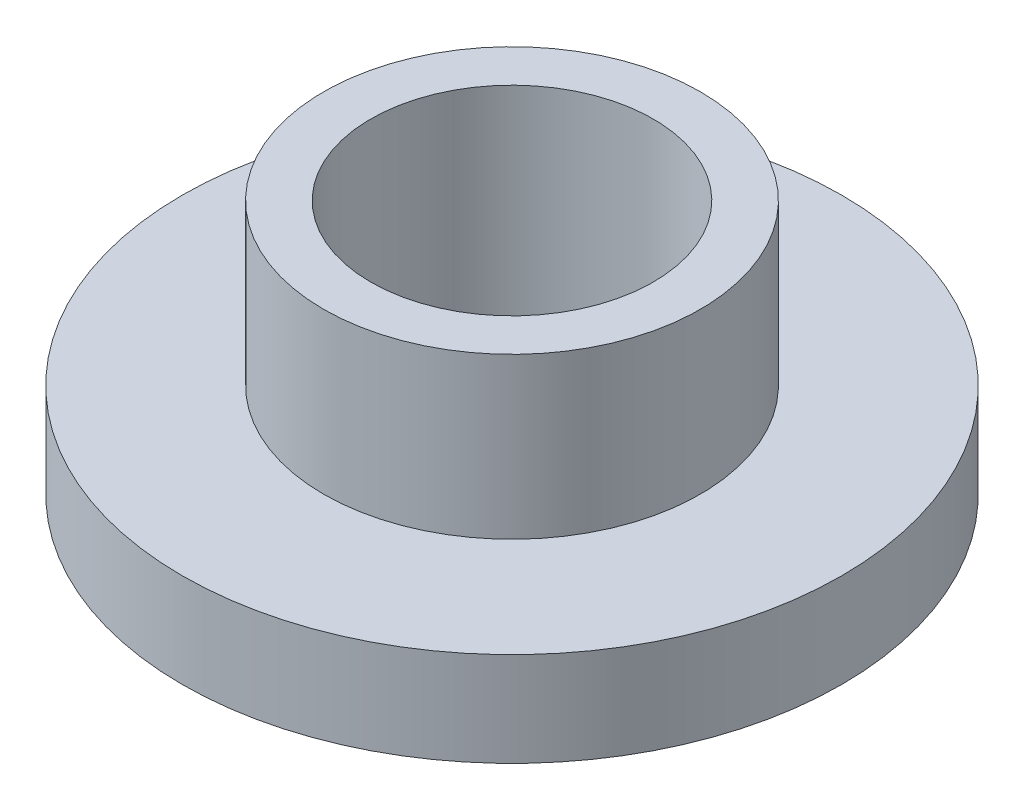
SolidWorks part; units mm, degrees
ref_plane "Front Plane" through (0, 0, 0) normal (0, 0, 1) x (1, 0, 0)
ref_plane "Top Plane" through (0, 0, 0) normal (0, 1, 0) x (1, 0, 0)
ref_plane "Right Plane" through (0, 0, 0) normal (1, 0, 0) x (0, 0, -1)
sketch "Sketch1" plane through (0, 0, 0) normal (0, 1, 0) x (1, 0, 0)
  circle A0 centre (0, 0) radius 7
  dimension "D1" = 14
extrude "Boss-Extrude1" add sketch "Sketch1" along normal blind 2 contours A0
sketch "Sketch2" plane through (0, 2, 0) normal (0, 1, 0) x (1, 0, 0)
  circle A0 centre (0, 0) radius 4
  dimension "D1" = 8
extrude "Boss-Extrude2" add sketch "Sketch2" along normal blind 3.4
sketch "Sketch3" plane through (0, 5.4, 0) normal (0, 1, 0) x (1, 0, 0)
  circle A0 centre (0, 0) radius 3
  dimension "D1" = 6
extrude "Cut-Extrude1" cut sketch "Sketch3" against normal through all
